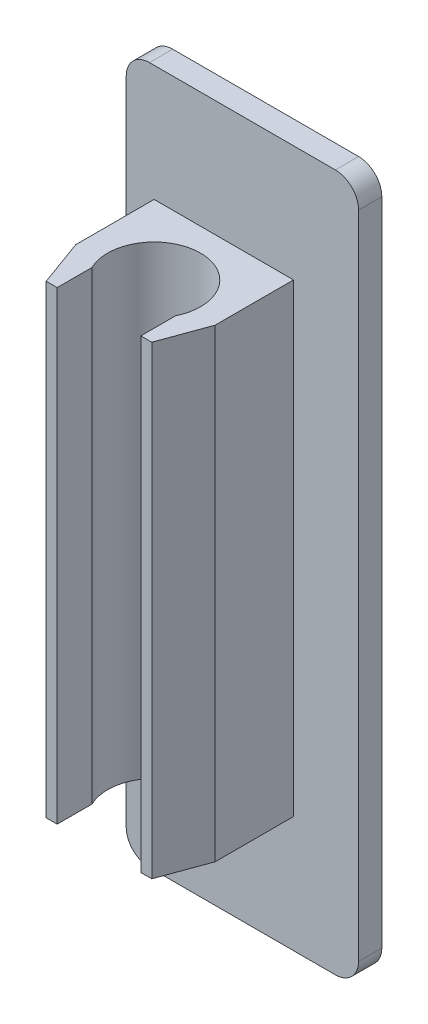
SolidWorks part; units mm, degrees
ref_plane "Front Plane" through (0, 0, 0) normal (0, 0, 1) x (1, 0, 0)
ref_plane "Top Plane" through (0, 0, 0) normal (0, 1, 0) x (1, 0, 0)
ref_plane "Right Plane" through (0, 0, 0) normal (1, 0, 0) x (0, 0, -1)
sketch "Sketch1" plane through (0, 0, 0) normal (0, 0, 1) x (1, 0, 0)
  line L1 (5, -15) -> (-5, -15)
  line L2 (5, -15) -> (5, 15)
  line L3 (5, 15) -> (-5, 15)
  line L4 (-5, -15) -> (-5, 15)
  line L5 (5, -15) -> (-5, 15) construction
  line L6 (5, 15) -> (-5, -15) construction
  point P0 (0, 0)
  dimension "D1" = 30
  dimension "D2" = 10
extrude "Boss-Extrude1" add sketch "Sketch1" along normal blind 1
sketch "Sketch3" plane through (0, 0, 0) normal (0, -1, 0) x (1, 0, 0)
  line L0 (-3.8, 1) -> (-3.8, 4.3718)
  line L1 (-5, 1) -> (5, 1) construction
  line L2 (-3.0721, 6.3718) -> (-2.6, 6.3718)
  line L3 (-2.6, 6.3718) -> (-2.6, 4.8718)
  line L4 (-0.8, 4) -> (-0.8, 1) construction
  line L5 (1, 6.3718) -> (1, 4.8718)
  line L8 (-5, 1) -> (-5, 0) construction
  line L9 (-3.8, 1) -> (2.2, 1)
  line L10 (-3.8, 4.3718) -> (-3.0721, 6.3718)
  line L11 (2.2, 1) -> (2.2, 4.3718)
  line L12 (2.2, 4.3718) -> (1.4721, 6.3718)
  line L13 (1.4721, 6.3718) -> (1, 6.3718)
  arc A0 (-2.6, 4.8718) -> (1, 4.8718) centre (-0.8, 4) ccw
  arc A1 (1, 4.8718) -> (-2.6, 4.8718) centre (-0.8, 4) ccw construction
  point P4 (-3.8, 6.3718)
  dimension "D1" = 4
  dimension "D2" = 3.6
  dimension "D3" = 1.5
  dimension "D4" = 6
  dimension "D5" = 3
  dimension "D6" = 1.2
  dimension "D7" = 2
  dimension "D8" = 20
extrude "Boss-Extrude2" add sketch "Sketch3" along normal mid plane 20
fillet "Fillet1" radius 1 4 edges at (5, 15, 0.5) (5, -15, 0.5) (-5, 15, 0.5) (-5, -15, 0.5)
